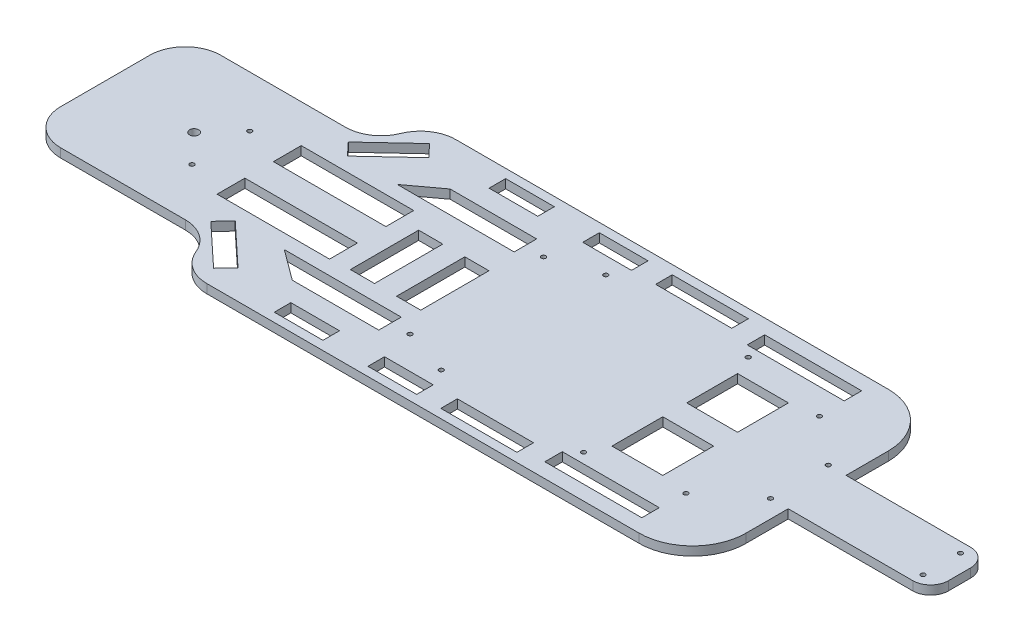
SolidWorks part; units mm, degrees
ref_plane "Front Plane" through (0, 0, 0) normal (0, 0, 1) x (1, 0, 0)
ref_plane "Top Plane" through (0, 0, 0) normal (0, 1, 0) x (1, 0, 0)
ref_plane "Right Plane" through (0, 0, 0) normal (1, 0, 0) x (0, 0, -1)
sketch "Sketch1" plane through (0, 0, 0) normal (0, 1, 0) x (1, 0, 0)
  line L0 (-112.4119, 0) -> (106.0661, 0) construction
  line L1 (0, -25) -> (0, 25)
  line L2 (20, 45) -> (90, 45)
  line L3 (127.081, 70) -> (370, 70)
  line L4 (400, 40) -> (400, 16.25)
  line L5 (127.081, -70) -> (370, -70)
  line L6 (20, -45) -> (90, -45)
  line L7 (400, 16.25) -> (470, 16.25)
  line L8 (480, 6.25) -> (480, -6.25)
  line L9 (470, -16.25) -> (400, -16.25)
  line L10 (400, -16.25) -> (400, -40)
  line L17 (97.9739, 38.6188) -> (121.5839, 60.672)
  line L18 (160, 55.6899) -> (187.3607, 55.6899)
  line L19 (160, 55.6899) -> (160, 65)
  line L20 (160, 65) -> (187.3607, 65)
  line L21 (187.3607, 55.6899) -> (187.3607, 65)
  line L22 (160, 55.6899) -> (187.3607, 65) construction
  line L23 (160, 65) -> (187.3607, 55.6899) construction
  line L24 (240, 55.6899) -> (212.6393, 55.6899)
  line L25 (240, 55.6899) -> (240, 65)
  line L26 (240, 65) -> (212.6393, 65)
  line L27 (212.6393, 55.6899) -> (212.6393, 65)
  line L28 (240, 55.6899) -> (212.6393, 65) construction
  line L29 (240, 65) -> (212.6393, 55.6899) construction
  line L30 (97.9739, 38.6188) -> (104.603, 31.5218)
  line L31 (121.5839, 60.672) -> (128.2129, 53.575)
  line L32 (104.603, 31.5218) -> (128.2129, 53.575)
  line L33 (121.5839, -60.672) -> (128.2129, -53.575)
  line L34 (86.5164, 23.6378) -> (149.7014, 23.6378)
  line L35 (86.5164, 23.6378) -> (86.5164, 8.0091)
  line L36 (86.5164, 8.0091) -> (149.7014, 8.0091)
  line L37 (149.7014, 23.6378) -> (149.7014, 8.0091)
  line L38 (86.5164, 23.6378) -> (149.7014, 8.0091) construction
  line L39 (86.5164, 8.0091) -> (149.7014, 23.6378) construction
  line L40 (348.5633, 35.2871) -> (320, 35.2871)
  line L41 (348.5633, 35.2871) -> (348.5633, 6.7238)
  line L42 (348.5633, 6.7238) -> (320, 6.7238)
  line L43 (320, 35.2871) -> (320, 6.7238)
  line L44 (348.5633, 35.2871) -> (320, 6.7238) construction
  line L45 (348.5633, 6.7238) -> (320, 35.2871) construction
  line L46 (363.2578, 51.9455) -> (308.767, 51.9455)
  line L47 (363.2578, 51.9455) -> (363.2578, 61.7538)
  line L48 (363.2578, 61.7538) -> (308.767, 61.7538)
  line L49 (308.767, 51.9455) -> (308.767, 61.7538)
  line L50 (363.2578, 51.9455) -> (308.767, 61.7538) construction
  line L51 (363.2578, 61.7538) -> (308.767, 51.9455) construction
  line L52 (97.9739, -38.6188) -> (121.5839, -60.672)
  line L53 (97.9739, -38.6188) -> (104.603, -31.5218)
  line L54 (104.603, -31.5218) -> (128.2129, -53.575)
  line L55 (160, -65) -> (187.3607, -55.6899) construction
  line L56 (160, -55.6899) -> (187.3607, -65) construction
  line L57 (187.3607, -55.6899) -> (187.3607, -65)
  line L58 (160, -65) -> (187.3607, -65)
  line L59 (160, -55.6899) -> (160, -65)
  line L60 (160, -55.6899) -> (187.3607, -55.6899)
  line L61 (240, -65) -> (212.6393, -55.6899) construction
  line L62 (240, -55.6899) -> (212.6393, -65) construction
  line L63 (212.6393, -55.6899) -> (212.6393, -65)
  line L64 (240, -65) -> (212.6393, -65)
  line L65 (240, -55.6899) -> (240, -65)
  line L66 (240, -55.6899) -> (212.6393, -55.6899)
  line L67 (363.2578, -61.7538) -> (308.767, -51.9455) construction
  line L68 (363.2578, -51.9455) -> (308.767, -61.7538) construction
  line L69 (308.767, -51.9455) -> (308.767, -61.7538)
  line L70 (363.2578, -61.7538) -> (308.767, -61.7538)
  line L71 (363.2578, -51.9455) -> (363.2578, -61.7538)
  line L72 (363.2578, -51.9455) -> (308.767, -51.9455)
  line L73 (348.5633, -6.7238) -> (320, -35.2871) construction
  line L74 (348.5633, -35.2871) -> (320, -6.7238) construction
  line L75 (320, -35.2871) -> (320, -6.7238)
  line L76 (348.5633, -6.7238) -> (320, -6.7238)
  line L77 (348.5633, -35.2871) -> (348.5633, -6.7238)
  line L78 (348.5633, -35.2871) -> (320, -35.2871)
  line L79 (86.5164, -8.0091) -> (149.7014, -23.6378) construction
  line L80 (86.5164, -23.6378) -> (149.7014, -8.0091) construction
  line L81 (149.7014, -23.6378) -> (149.7014, -8.0091)
  line L82 (86.5164, -8.0091) -> (149.7014, -8.0091)
  line L83 (86.5164, -23.6378) -> (86.5164, -8.0091)
  line L84 (86.5164, -23.6378) -> (149.7014, -23.6378)
  arc A0 (0, 25) -> (20, 45) centre (20, 25) cw
  arc A1 (90, 45) -> (108.5405, 57.5) centre (90, 65) ccw
  arc A2 (108.5405, 57.5) -> (127.081, 70) centre (127.081, 50) cw
  arc A3 (370, 70) -> (400, 40) centre (370, 40) cw
  arc A4 (370, -70) -> (400, -40) centre (370, -40) ccw
  arc A5 (108.5405, -57.5) -> (127.081, -70) centre (127.081, -50) ccw
  arc A6 (90, -45) -> (108.5405, -57.5) centre (90, -65) cw
  arc A7 (0, -25) -> (20, -45) centre (20, -25) ccw
  arc A8 (470, -16.25) -> (480, -6.25) centre (470, -6.25) ccw
  arc A9 (480, 6.25) -> (470, 16.25) centre (470, 6.25) ccw
  point P16 (0, 0)
  point P36 (480, -16.25)
  point P54 (173.6804, 60.3449)
  point P63 (226.3196, 60.3449)
  point P72 (118.1089, 15.8234)
  point P73 (334.2816, 21.0055)
  point P82 (336.0124, 56.8496)
  point P91 (173.6804, -60.3449)
  point P96 (226.3196, -60.3449)
  point P101 (336.0124, -56.8496)
  point P106 (334.2816, -21.0055)
  point P111 (118.1089, -15.8234)
  dimension "D5" = 30
  dimension "D6" = 20
  dimension "D7" = 20
  dimension "D8" = 80
  dimension "D10" = 10
  dimension "D1" = 32.5
  dimension "D2" = 400
  dimension "D3" = 90
  dimension "D4" = 45
  dimension "D9" = 80
  dimension "D22" = 5
extrude "Boss-Extrude2" add sketch "Sketch1" along normal blind 5
hole_wizard "M3x0.5 Tapped Hole1" positions "Sketch6" profile "Sketch7" tap size "M3x0.5" standard "JIS" end condition through all
sketch "Sketch6" plane through (0, 5, 0) normal (0, 1, 0) x (1, 0, 0)
  line L0 (-40.2024, 0) -> (435.5418, 0) construction
  line L1 (390, 16.25) -> (390, -16.25) construction
  line L3 (363.7721, 37.5) -> (363.7721, -37.5) construction
  line L5 (235.0227, 46.25) -> (315.0227, 46.25) construction
  line L6 (315.0227, 46.25) -> (315.0227, -46.25) construction
  line L7 (315.0227, -46.25) -> (235.0227, -46.25) construction
  line L8 (235.0227, -46.25) -> (235.0227, 46.25) construction
  line L10 (208.7721, 37.5) -> (208.7721, -37.5) construction
  line L11 (65, 16.25) -> (65, -16.25) construction
  line L12 (400, 16.25) -> (400, 40) construction
  line L13 (0, 25) -> (0, -25) construction
  line L14 (470, 10.5) -> (470, -10.5) construction
  line L16 (480, -6.25) -> (480, 6.25) construction
  point P7 (390, 16.25)
  point P8 (390, -16.25)
  point P11 (363.7721, 37.5)
  point P12 (363.7721, -37.5)
  point P16 (235.0227, 46.25)
  point P17 (315.0227, 46.25)
  point P19 (315.0227, -46.25)
  point P21 (235.0227, -46.25)
  point P30 (208.7721, 37.5)
  point P31 (208.7721, -37.5)
  point P34 (65, 16.25)
  point P35 (65, -16.25)
  point P65 (470, 10.5)
  point P67 (470, -10.5)
  dimension "D1" = 80
  dimension "D2" = 92.5
  dimension "D4" = 75
  dimension "D5" = 32.5
  dimension "D7" = 10
  dimension "D8" = 65
  dimension "D9" = 10.5
  dimension "D10" = 10
  dimension "D3" = 2
  dimension "D6" = 2
sketch "Sketch7" plane through (470, 5, 10.5) normal (1, 0, 0) x (0, 0, 1)
  line L0 (0, 0) -> (0, 5)
  line L1 (0, 5) -> (1.525, 5)
  line L2 (1.25, 4.725) -> (1.25, 0)
  line L5 (1.25, 0) -> (0, 0)
  line L7 (1.525, 5) -> (1.25, 4.725)
  line L8 (-1.525, 5) -> (-1.25, 4.725) construction
  line L11 (0, -6.35) -> (0, 107.95) construction
  dimension "Thru Tap Drill Dia." = 2.5
  dimension "Thru Tap Drill Depth" = 5
  dimension "Far C'Sink Dia." = 3.05
  dimension "Far C'Sink Angle" = 90
cosmetic thread "Hole Thread1" parameters "D2"=3
cosmetic thread "Hole Thread2" parameters "D2"=3
cosmetic thread "Hole Thread3" parameters "D2"=3
cosmetic thread "Hole Thread4" parameters "D2"=3
cosmetic thread "Hole Thread5" parameters "D2"=3
cosmetic thread "Hole Thread6" parameters "D2"=3
cosmetic thread "Hole Thread7" parameters "D2"=3
cosmetic thread "Hole Thread8" parameters "D2"=3
cosmetic thread "Hole Thread9" parameters "D2"=3
cosmetic thread "Hole Thread10" parameters "D2"=3
cosmetic thread "Hole Thread11" parameters "D2"=3
cosmetic thread "Hole Thread12" parameters "D2"=3
cosmetic thread "Hole Thread14" parameters "D2"=3
cosmetic thread "Hole Thread15" parameters "D2"=3
hole_wizard "1/4-20 Tapped Hole1" positions "Sketch11" profile "Sketch9" tap size "1/4-20" standard "ANSI Inch" end condition through all
sketch "Sketch11" plane through (0, 5, 0) normal (0, 1, 0) x (1, 0, 0)
  point P0 (50, 0)
  dimension "D1" = 50
sketch "Sketch9" plane through (50, 5, 0) normal (1, 0, 0) x (0, 0, 1)
  line L0 (0, 0) -> (0, 5)
  line L1 (0, 5) -> (3.81, 5)
  line L2 (2.5527, 3.7427) -> (2.5527, 0)
  line L5 (2.5527, 0) -> (0, 0)
  line L7 (3.81, 5) -> (2.5527, 3.7427)
  line L8 (-3.81, 5) -> (-2.5527, 3.7427) construction
  line L11 (0, -6.35) -> (0, 107.95) construction
  dimension "Thru Tap Drill Dia." = 5.1054
  dimension "Thru Tap Drill Depth" = 5
  dimension "Far C'Sink Dia." = 7.62
  dimension "Far C'Sink Angle" = 90
cosmetic thread "Hole Thread13" parameters "D2"=6.35
sketch "Sketch12" plane through (0, 5, 0) normal (0, 1, 0) x (1, 0, 0)
  line L0 (240, 65) -> (212.6393, 65) construction
  line L1 (174.2026, 15.4793) -> (160.635, 15.4793)
  line L2 (174.2026, 15.4793) -> (174.2026, -22.8724)
  line L3 (174.2026, -22.8724) -> (160.635, -22.8724)
  line L4 (160.635, 15.4793) -> (160.635, -22.8724)
  line L5 (174.2026, 15.4793) -> (160.635, -22.8724) construction
  line L6 (174.2026, -22.8724) -> (160.635, 15.4793) construction
  line L7 (200.1503, 15.4793) -> (186.5826, 15.4793)
  line L8 (200.1503, 15.4793) -> (200.1503, -22.8724)
  line L9 (200.1503, -22.8724) -> (186.5826, -22.8724)
  line L10 (186.5826, 15.4793) -> (186.5826, -22.8724)
  line L11 (200.1503, 15.4793) -> (186.5826, -22.8724) construction
  line L12 (200.1503, -22.8724) -> (186.5826, 15.4793) construction
  line L13 (253.5803, 55.6899) -> (296.3535, 55.6899)
  line L14 (253.5803, 55.6899) -> (253.5803, 65)
  line L15 (253.5803, 65) -> (296.3535, 65)
  line L16 (296.3535, 55.6899) -> (296.3535, 65)
  line L17 (253.5803, 55.6899) -> (296.3535, 65) construction
  line L18 (253.5803, 65) -> (296.3535, 55.6899) construction
  line L19 (212.6393, 55.6899) -> (240, 55.6899) construction
  line L20 (-13.8224, 0) -> (528.253, 0) construction
  line L21 (253.5803, -65) -> (296.3535, -55.6899) construction
  line L22 (253.5803, -55.6899) -> (296.3535, -65) construction
  line L23 (296.3535, -55.6899) -> (296.3535, -65)
  line L24 (253.5803, -65) -> (296.3535, -65)
  line L25 (253.5803, -55.6899) -> (253.5803, -65)
  line L26 (253.5803, -55.6899) -> (296.3535, -55.6899)
  line L27 (132.3602, 31.7094) -> (149.4712, 44.3545)
  line L28 (149.4712, 44.3545) -> (198.0604, 44.3545)
  line L29 (198.0604, 44.3545) -> (198.0604, 31.7094)
  line L30 (198.0604, 31.7094) -> (132.3602, 31.7094)
  line L31 (198.0604, -31.7094) -> (132.3602, -31.7094)
  line L32 (198.0604, -44.3545) -> (198.0604, -31.7094)
  line L33 (149.4712, -44.3545) -> (198.0604, -44.3545)
  line L34 (132.3602, -31.7094) -> (149.4712, -44.3545)
  point P4 (167.4188, -3.6965)
  point P9 (193.3665, -3.6965)
  point P14 (274.9669, 60.3449)
  point P26 (274.9669, -60.3449)
extrude "Cut-Extrude1" cut sketch "Sketch12" against normal up to surface (5 mm away) up to face at (50, 0, 3.81)
equation "\"6ץ5\"=7"
